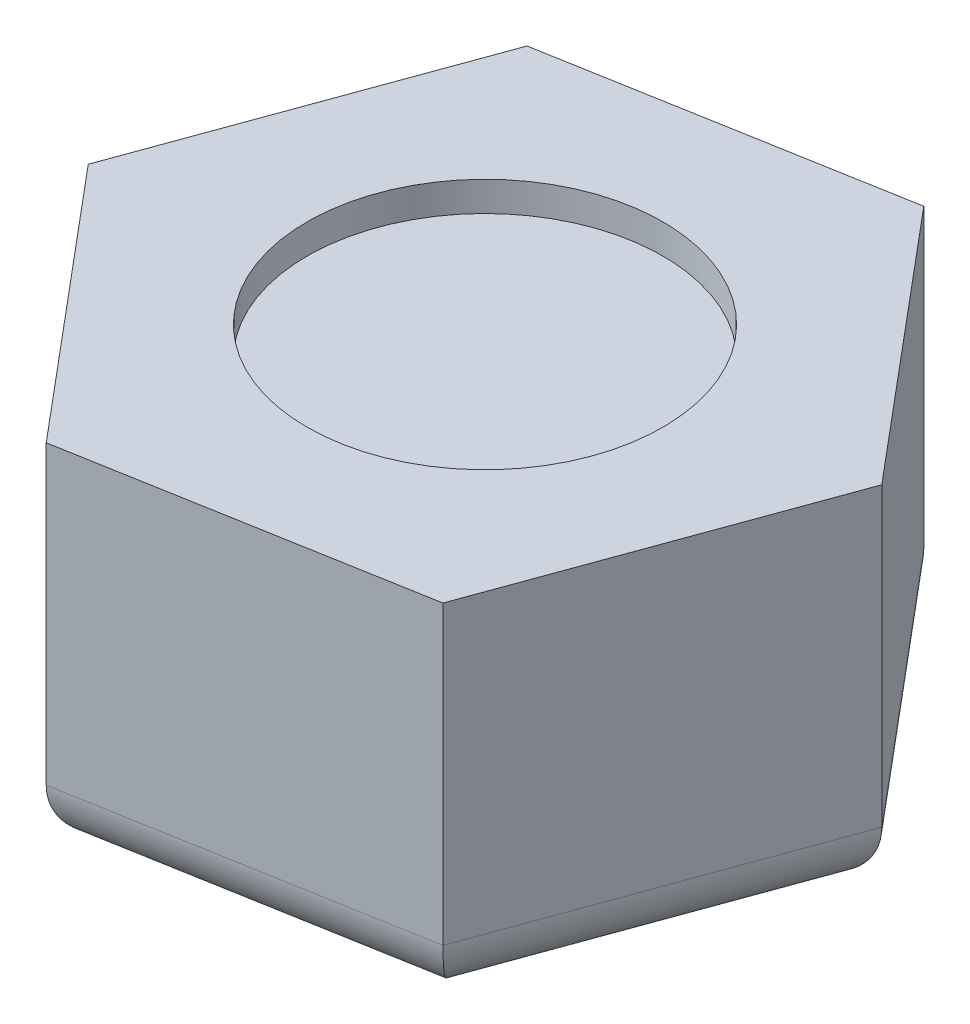
SolidWorks part; units mm, degrees
ref_plane "Front Plane" through (0, 0, 0) normal (0, 0, 1) x (1, 0, 0)
ref_plane "Top Plane" through (0, 0, 0) normal (0, 1, 0) x (1, 0, 0)
ref_plane "Right Plane" through (0, 0, 0) normal (1, 0, 0) x (0, 0, -1)
sketch "Sketch1" plane through (0, 0, 0) normal (0, 1, 0) x (1, 0, 0)
  line L1 (3712.9679, -4421.2219) -> (5685.3744, 1004.9136)
  line L2 (5685.3744, 1004.9136) -> (1972.4065, 5426.1354)
  line L3 (1972.4065, 5426.1354) -> (-3712.9679, 4421.2219)
  line L4 (-3712.9679, 4421.2219) -> (-5685.3744, -1004.9136)
  line L5 (-5685.3744, -1004.9136) -> (-1972.4065, -5426.1354)
  line L6 (-1972.4065, -5426.1354) -> (3712.9679, -4421.2219)
  circle A0 centre (0, 0) radius 5000 construction
  dimension "D1" = 10000
extrude "Boss-Extrude2" add sketch "Sketch1" along normal blind 6000
fillet "Fillet2" radius 1000 6 edges at (-3828.8905, 0, 3215.5245) (-4699.1711, 0, -1708.1541) (-870.2807, 0, -4923.6787) (3828.8905, 0, -3215.5245) (4699.1711, 0, 1708.1541) (870.2807, 0, 4923.6787)
sketch "Sketch4" plane through (0, 6000, 0) normal (0, 1, 0) x (1, 0, 0)
  circle A0 centre (0, 0) radius 3000
  dimension "D1" = 6000
extrude "Cut-Extrude2" cut sketch "Sketch4" against normal blind 500
sketch "Sketch5" plane through (4699.1711, 0, 1708.1541) normal (0.9398, 0, 0.3416) x (0.3416, 0, -0.9398)
